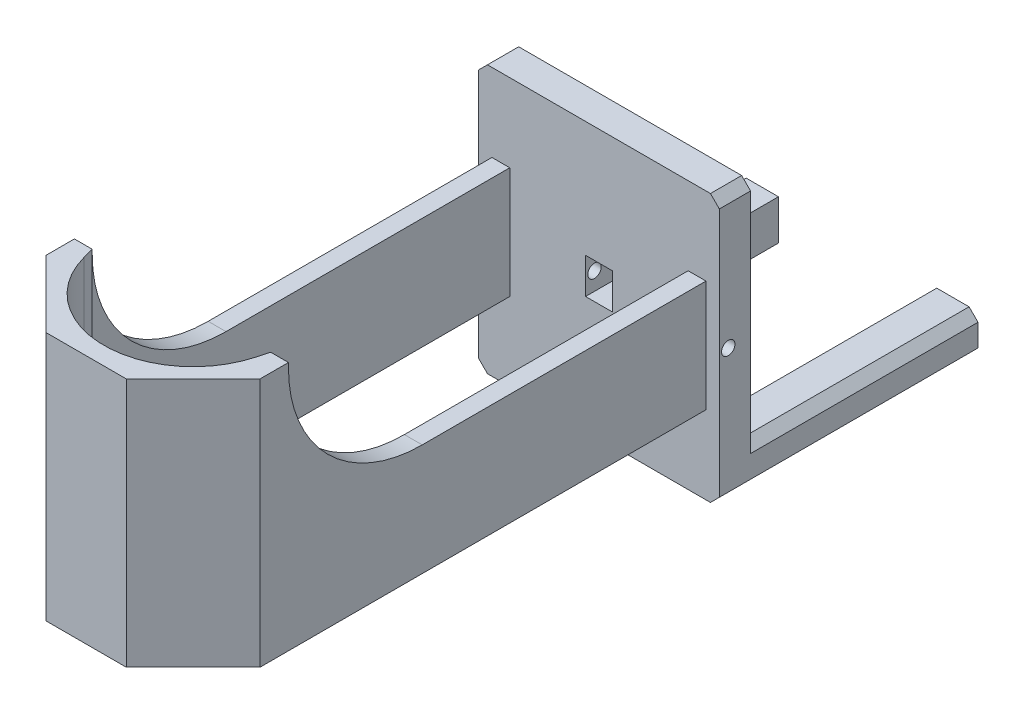
SolidWorks part; units mm, degrees
ref_plane "Front Plane" through (0, 0, 0) normal (0, 0, 1) x (1, 0, 0)
ref_plane "Top Plane" through (0, 0, 0) normal (0, 1, 0) x (1, 0, 0)
ref_plane "Right Plane" through (0, 0, 0) normal (1, 0, 0) x (0, 0, -1)
sketch "Sketch1" plane through (0, 0, 0) normal (0, 0, 1) x (1, 0, 0)
  line L0 (54, 2) -> (54, 7) construction
  line L1 (54, 7) -> (52, 9) construction
  line L2 (52, 9) -> (44.75, 9) construction
  line L3 (44.75, 9) -> (44.75, 0) construction
  line L4 (44.75, 0) -> (52, 0) construction
  line L5 (52, 0) -> (54, 2) construction
  line L6 (0, 7) -> (0, 2) construction
  line L7 (0, 2) -> (2, 0) construction
  line L8 (2, 0) -> (9.25, 0) construction
  line L9 (9.25, 0) -> (9.25, 9) construction
  line L10 (9.25, 9) -> (2, 9) construction
  line L11 (2, 9) -> (0, 7) construction
  line L12 (37.6, 51) -> (52, 51) construction
  line L13 (52, 51) -> (54, 53) construction
  line L14 (54, 53) -> (54, 58) construction
  line L15 (54, 58) -> (52, 60) construction
  line L16 (52, 60) -> (2, 60) construction
  line L17 (2, 60) -> (0, 58) construction
  line L18 (0, 58) -> (0, 53) construction
  line L19 (0, 53) -> (2, 51) construction
  line L20 (2, 51) -> (16.4, 51) construction
  line L21 (16.4, 51) -> (37.6, 51) construction
  line L22 (54, 2) -> (54, 7)
  line L23 (54, 7) -> (52, 9)
  line L24 (52, 9) -> (44.75, 9)
  line L25 (44.75, 9) -> (44.75, 0)
  line L26 (44.75, 0) -> (52, 0)
  line L27 (52, 0) -> (54, 2)
  line L28 (0, 7) -> (0, 2)
  line L29 (0, 2) -> (2, 0)
  line L30 (2, 0) -> (9.25, 0)
  line L31 (9.25, 0) -> (9.25, 9)
  line L32 (9.25, 9) -> (2, 9)
  line L33 (2, 9) -> (0, 7)
  line L34 (37.6, 51) -> (52, 51)
  line L35 (52, 51) -> (54, 53)
  line L36 (54, 53) -> (54, 58)
  line L37 (54, 58) -> (52, 60)
  line L38 (52, 60) -> (2, 60)
  line L39 (2, 60) -> (0, 58)
  line L40 (0, 58) -> (0, 53)
  line L41 (0, 53) -> (2, 51)
  line L42 (2, 51) -> (16.4, 51)
  line L43 (16.4, 51) -> (37.6, 51)
extrude "Boss-Extrude1" add sketch "Sketch1" along normal blind 5 contours L38 L39 L40 L41 L42 L43 L34 L35 L36 L37
sketch "Sketch2" plane through (0, 0, -51) normal (0, 0, 1) x (1, 0, 0)
  line L0 (0, 7) -> (0, 2) construction
  line L1 (0, 2) -> (2, 0) construction
  line L2 (2, 0) -> (9.25, 0) construction
  line L3 (9.25, 0) -> (9.25, 9) construction
  line L4 (9.25, 9) -> (2, 9) construction
  line L5 (2, 9) -> (0, 7) construction
  line L6 (54, 2) -> (54, 7) construction
  line L7 (54, 7) -> (52, 9) construction
  line L8 (52, 9) -> (44.75, 9) construction
  line L9 (44.75, 9) -> (44.75, 0) construction
  line L10 (44.75, 0) -> (52, 0) construction
  line L11 (52, 0) -> (54, 2) construction
  line L12 (0, 7) -> (0, 2)
  line L13 (0, 2) -> (2, 0)
  line L14 (2, 0) -> (9.25, 0)
  line L15 (9.25, 0) -> (9.25, 9)
  line L16 (9.25, 9) -> (2, 9)
  line L17 (2, 9) -> (0, 7)
  line L18 (54, 2) -> (54, 7)
  line L19 (54, 7) -> (52, 9)
  line L20 (52, 9) -> (44.75, 9)
  line L21 (44.75, 9) -> (44.75, 0)
  line L22 (44.75, 0) -> (52, 0)
  line L23 (52, 0) -> (54, 2)
extrude "Boss-Extrude2" add sketch "Sketch2" along normal blind 56 separate body
sketch "Sketch8" plane through (0, 0, 5) normal (0, 0, 1) x (1, 0, 0)
  line L0 (0, 2) -> (0, 58)
  line L1 (2, 60) -> (52, 60)
  line L2 (54, 58) -> (54, 2)
  line L3 (52, 0) -> (2, 0)
  line L4 (52, 60) -> (2, 60) construction
  line L5 (54, 53) -> (54, 58) construction
  line L6 (0, 58) -> (2, 60)
  line L7 (52, 60) -> (54, 58)
  line L8 (54, 2) -> (52, 0)
  line L9 (2, 0) -> (0, 2)
  point P0 (0, 0)
  point P1 (0, 60)
  point P4 (54, 60)
  point P5 (54, 0)
  dimension "D1" = 0
  dimension "D2" = 0
extrude "Boss-Extrude3" add sketch "Sketch8" along normal blind 2 and the other way blind 5
sketch "Sketch9" plane through (0, 0, 7) normal (0, 0, 1) x (1, 0, 0)
  line L1 (24, 34) -> (30, 34)
  line L2 (24, 34) -> (24, 26)
  line L3 (24, 26) -> (30, 26)
  line L4 (30, 34) -> (30, 26)
  line L5 (24, 34) -> (30, 26) construction
  line L6 (24, 26) -> (30, 34) construction
  point P0 (27, 30)
  dimension "D1" = 8
  dimension "D2" = 6
  dimension "D3" = 27
  dimension "D4" = 30
extrude "Cut-Extrude3" cut sketch "Sketch9" against normal blind 6
sketch "Sketch10" plane through (30, 0, 0) normal (-1, 0, 0) x (0, 0, 1)
  line L0 (7, 58) -> (7, 2) construction
  circle A0 centre (5, 30) radius 1.5
  dimension "D1" = 3
  dimension "D2" = 2
  dimension "D3" = 30
extrude "Cut-Extrude4" cut sketch "Sketch10" against normal through all both and the other way through all
sketch "Sketch3" plane through (0, 0, -51) normal (0, 0, 1) x (1, 0, 0)
  circle A0 centre (4.5, 4.5) radius 2.15
  circle A1 centre (4.5, 55.5) radius 2.15
  circle A2 centre (49.5, 55.5) radius 2.15
  circle A3 centre (49.5, 4.5) radius 2.15
  circle A4 centre (4.5, 24.5) radius 2.15
  circle A5 centre (49.5, 24.5) radius 2.15
  dimension "D1" = 4.3
  dimension "D2" = 4.3
  dimension "D3" = 4.3
  dimension "D4" = 4.3
  dimension "D13" = 4.3
  dimension "D14" = 4.3
  dimension "D5" = 51
  dimension "D6" = 0
  dimension "D7" = 45
  dimension "D8" = 51
  dimension "D9" = 45
  dimension "D10" = 0
  dimension "D11" = 4.5
  dimension "D12" = 4.5
  dimension "D15" = 31
  dimension "D16" = 0
  dimension "D17" = 0
  dimension "D18" = 0
sketch "Sketch5" plane through (0, 60, 0) normal (0, 1, 0) x (1, 0, 0)
  line L0 (32.6, 5) -> (21.4, 5)
  line L5 (37.6, 10) -> (37.6, 46)
  line L8 (37.6, 10) -> (32.6, 5)
  line L9 (27, 71.4989) -> (27, -28.5011) construction
  line L11 (16.4, 10) -> (21.4, 5)
  line L12 (16.4, 10) -> (16.4, 46)
  line L14 (16.4, 46) -> (37.6, 46)
sketch3d "3DSketch1" plane through (0, 0, 0) normal (0, 0, 1) x (1, 0, 0)
  dimension "D1" = 30
sketch3d "3DSketch2" plane through (0, 0, 0) normal (0, 0, 1) x (1, 0, 0)
  dimension "D1" = 27
sketch3d "3DSketch3" plane through (0, 0, 0) normal (0, 0, 1) x (1, 0, 0)
  dimension "D1" = 2
sketch "Sketch11" plane through (0, 30, 0) normal (0, 1, 0) x (1, 0, 0)
  line L0 (52, 56) -> (2, 56) construction
  line L2 (27, 71.4989) -> (27, -28.5011) construction
  line L3 (3, -7) -> (51, -7)
  line L4 (51, -7) -> (51, -122)
  line L5 (51, -122) -> (3, -122)
  line L6 (3, -122) -> (3, -7)
  line L8 (52, -7) -> (2, -7) construction
  circle A0 centre (27, -98) radius 20 construction
  dimension "D1" = 40
  dimension "D2" = 154
  dimension "D3" = 0
  dimension "D4" = 24
  dimension "D5" = 48
  dimension "D6" = 24
  dimension "D7" = 0
extrude "Boss-Extrude4" add sketch "Sketch11" along normal blind 43.5 and the other way blind 12.5 contours L4 L5 L6 L3
sketch "Sketch12" plane through (0, 73.5, 0) normal (0, 1, 0) x (1, 0, 0)
  line L0 (3, -122) -> (3, -7) construction
  line L1 (52, 56) -> (2, 56) construction
  line L2 (52, -7) -> (51, -7) construction
  line L4 (7, -100.633) -> (7, -7)
  line L5 (7, -7) -> (47, -7)
  line L6 (47, -100.633) -> (47, -7)
  line L7 (51, -7) -> (51, -122) construction
  line L8 (7.6815, -103.1764) -> (7, -100.633)
  line L9 (46.3185, -103.1764) -> (47, -100.633)
  line L10 (27, 71.4989) -> (27, -28.5011) construction
  arc A0 (7.6815, -103.1764) -> (46.3185, -103.1764) centre (27, -98) ccw
  point P1 (0, 0)
  point P6 (0, 0)
  dimension "D1" = 40
  dimension "D4" = 0
  dimension "D8" = 0
  dimension "D2" = 24
  dimension "D3" = 154
  dimension "D5" = 4
  dimension "D6" = 4
  dimension "D9" = 15
extrude "Cut-Extrude5" cut sketch "Sketch12" against normal through all
sketch "Sketch13" plane through (27, 0, 0) normal (1, 0, 0) x (0, 0, -1)
  line L0 (-7, 73.5) -> (-122, 73.5) construction
  line L1 (-7, 42.5) -> (-70.633, 42.5)
  line L2 (-7, 42.5) -> (-7, 73.5)
  line L3 (-7, 73.5) -> (-100.633, 73.5)
  line L4 (-100.633, 72.5) -> (-100.633, 73.5)
  line L6 (-100.633, 17.5) -> (-100.633, 73.5) construction
  line L7 (-7, 17.5) -> (-122, 17.5) construction
  line L8 (-7, 58) -> (-7, 60) construction
  arc A0 (-100.633, 72.5) -> (-70.633, 42.5) centre (-70.633, 72.5) ccw
  dimension "D5" = 30
  dimension "D1" = 0
  dimension "D2" = 0
  dimension "D3" = 25
  dimension "D4" = 0
extrude "Cut-Extrude6" cut sketch "Sketch13" against normal through all both and the other way through all
chamfer "Chamfer1" distance 15 angle 45 1 edges at (3, 45.5, 122)
chamfer "Chamfer2" distance 15 angle 45 1 edges at (51, 45.5, 122)
